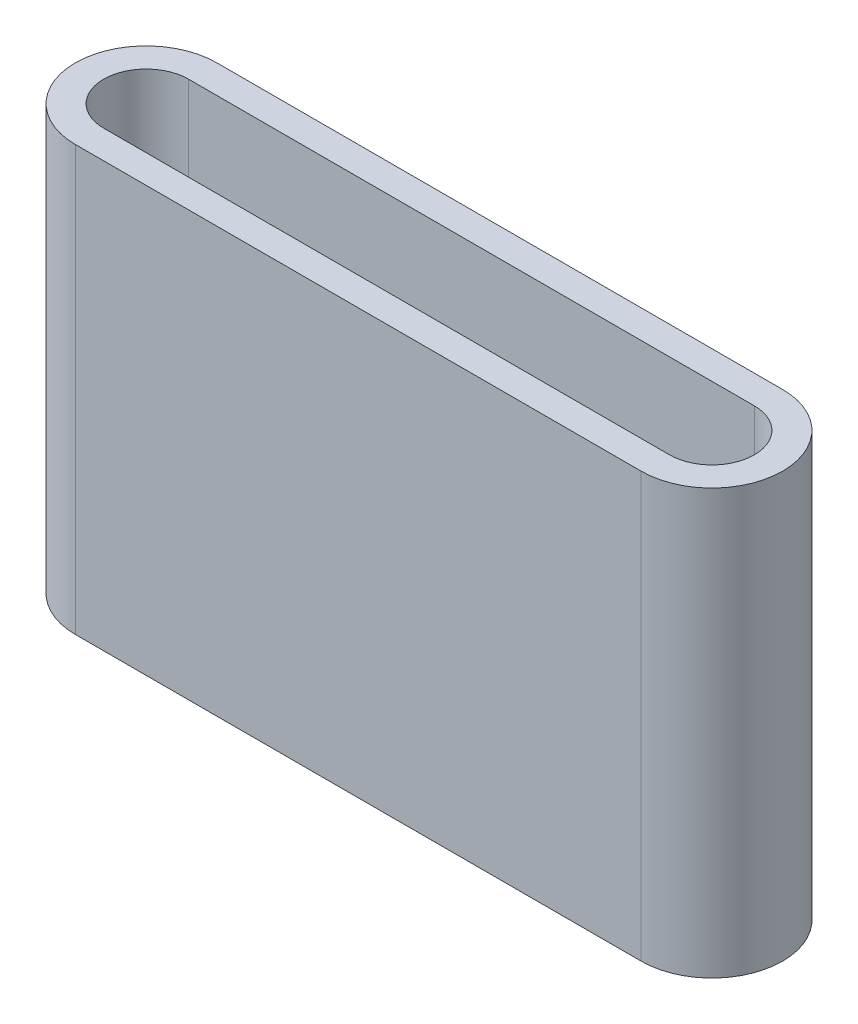
SolidWorks part; units mm, degrees
ref_plane "前视基准面" through (0, 0, 0) normal (0, 0, 1) x (1, 0, 0)
ref_plane "上视基准面" through (0, 0, 0) normal (0, 1, 0) x (1, 0, 0)
ref_plane "右视基准面" through (0, 0, 0) normal (1, 0, 0) x (0, 0, -1)
other "Configuration Table"
sketch "草图1" plane through (0, 0, 0) normal (0, 1, 0) x (1, 0, 0)
  line L0 (-50.2058, 0) -> (49.7942, 0) construction
  line L1 (-50.2058, 12.5) -> (49.7942, 12.5)
  line L2 (-50.2058, -12.5) -> (49.7942, -12.5)
  arc A0 (-50.2058, 12.5) -> (-50.2058, -12.5) centre (-50.2058, 0) ccw
  arc A1 (49.7942, -12.5) -> (49.7942, 12.5) centre (49.7942, 0) ccw
  point P3 (-0.2058, 0)
  dimension "D1" = 100
  dimension "D2" = 25
extrude "凸台-拉伸1" add sketch "草图1" along normal blind 20
sketch "草图2" plane through (0, 20, 0) normal (0, 1, 0) x (1, 0, 0)
  line L2 (-50.2058, -12.5) -> (49.7942, -12.5)
  line L3 (49.7942, 12.5) -> (-50.2058, 12.5)
  line L4 (-50.2058, -12.5) -> (49.7942, -12.5)
  line L5 (49.7942, 12.5) -> (-50.2058, 12.5)
  arc A2 (-50.2058, 12.5) -> (-50.2058, -12.5) centre (-50.2058, 0) ccw
  arc A3 (49.7942, -12.5) -> (49.7942, 12.5) centre (49.7942, 0) ccw
  arc A4 (-50.2058, 12.5) -> (-50.2058, -12.5) centre (-50.2058, 0) ccw
  arc A5 (49.7942, -12.5) -> (49.7942, 12.5) centre (49.7942, 0) ccw
  dimension "D1" = 0
extrude "拉伸-薄壁1" add sketch "草图2" along normal blind 55 thin thin type one direction reverse wall 5
